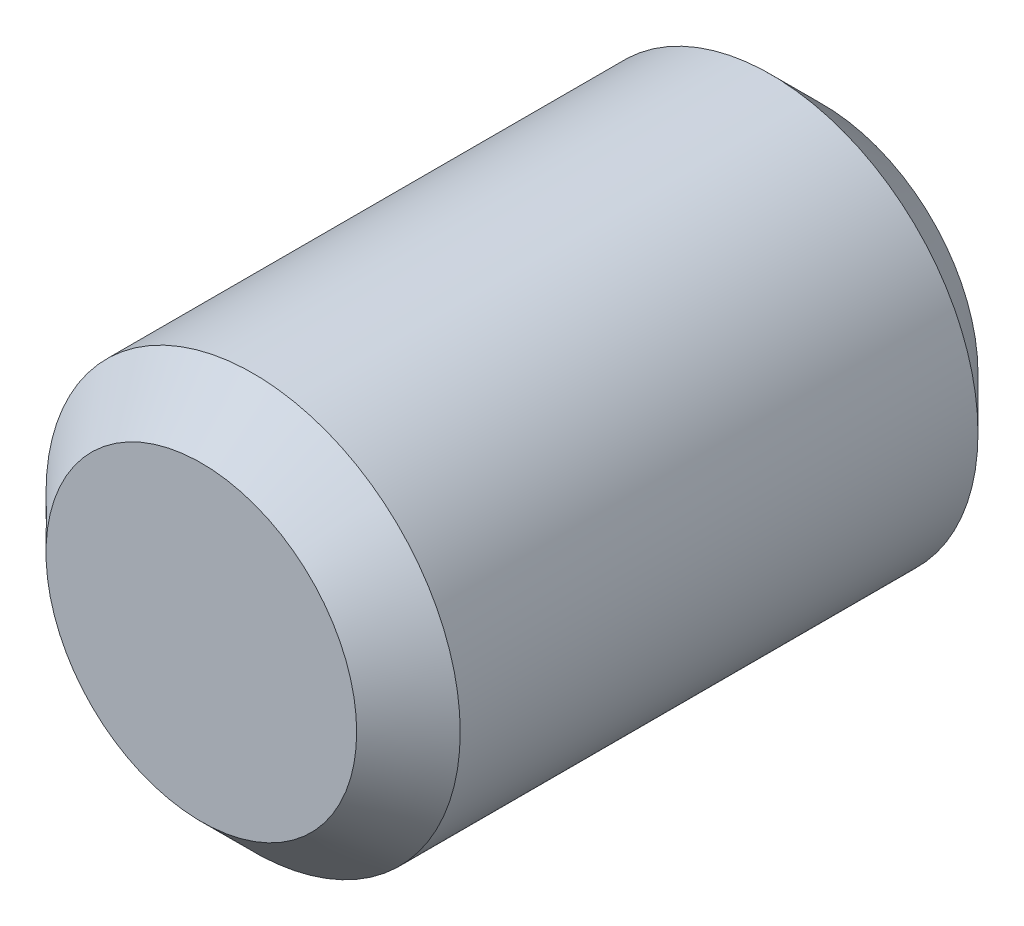
SolidWorks part; units mm, degrees
material "Plain Carbon Steel"
ref_plane "Спереди" through (0, 0, 0) normal (0, 0, 1) x (1, 0, 0)
ref_plane "Сверху" through (0, 0, 0) normal (0, 1, 0) x (1, 0, 0)
ref_plane "Справа" through (0, 0, 0) normal (1, 0, 0) x (0, 0, -1)
sketch "Sketch1" plane through (0, 0, 0) normal (0, 0, 1) x (1, 0, 0)
  circle A0 centre (0, 0) radius 4
  dimension "D1" = 8
extrude "Extrude1" add sketch "Sketch1" along normal mid plane 12
chamfer "Chamfer1" distance 1 angle 45 2 edges at (4, 0, -6) (4, 0, 6)
